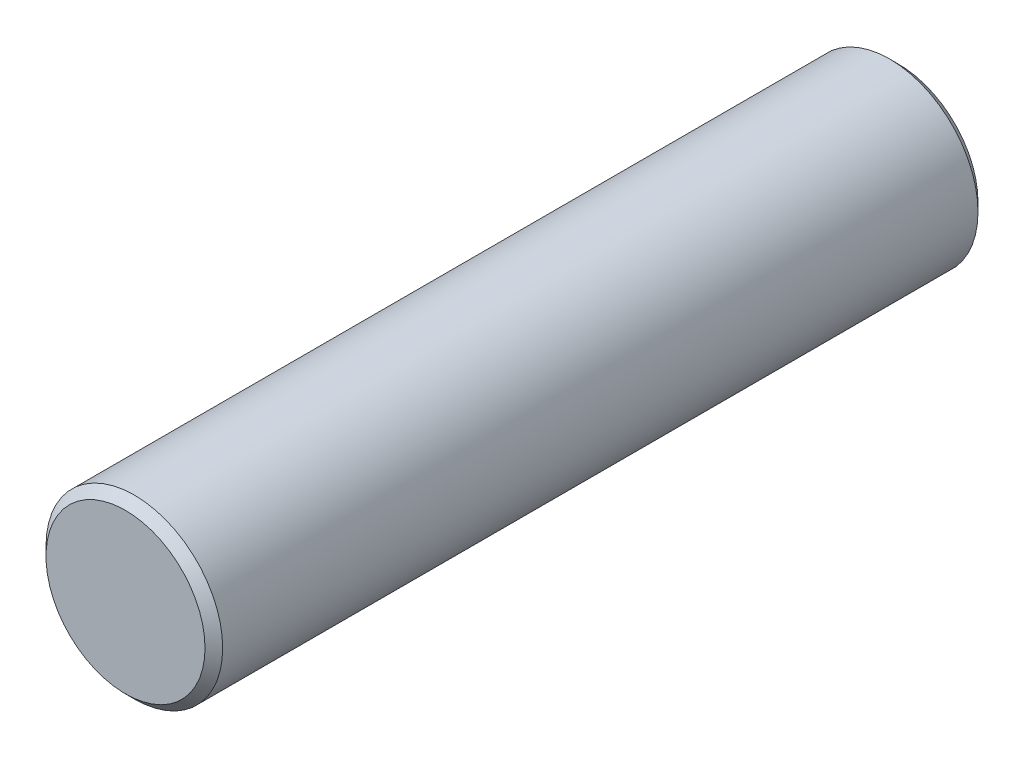
SolidWorks part; units mm, degrees
material "Chrome Stainless Steel"
ref_plane "Front Plane" through (0, 0, 0) normal (0, 0, 1) x (1, 0, 0)
ref_plane "Top Plane" through (0, 0, 0) normal (0, 1, 0) x (1, 0, 0)
ref_plane "Right Plane" through (0, 0, 0) normal (1, 0, 0) x (0, 0, -1)
sketch "Sketch1" plane through (0, 0, 0) normal (0, 0, 1) x (1, 0, 0)
  circle A0 centre (0, 0) radius 20
  dimension "D1" = 40
extrude "Extrude1" add sketch "Sketch1" along normal blind 175
chamfer "Chamfer1" distance 2 angle 45 2 edges at (20, 0, 0) (20, 0, 175)
